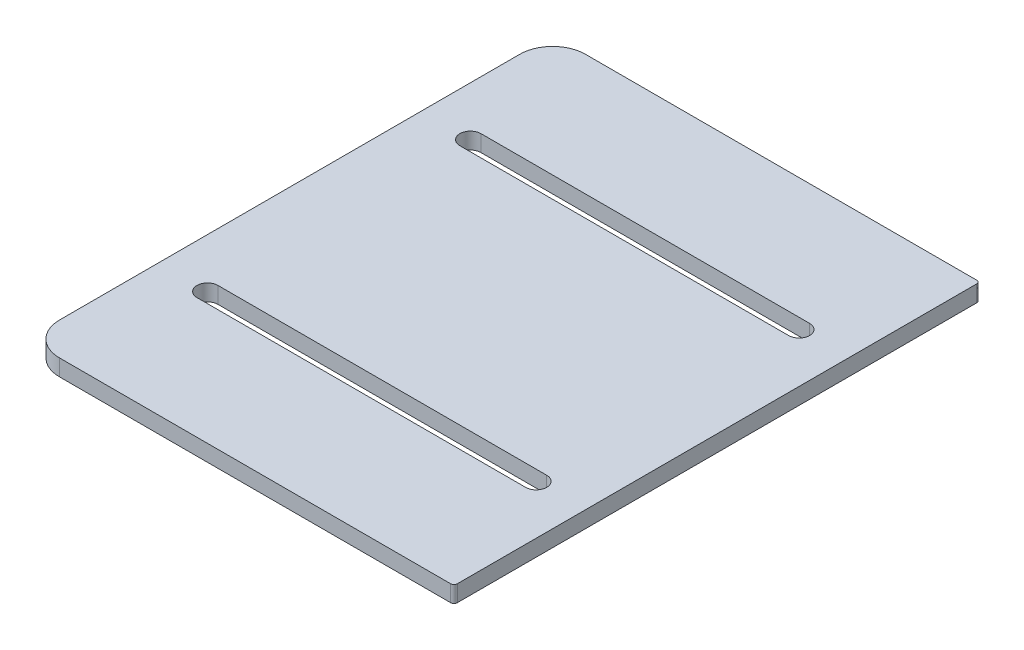
SolidWorks part; units mm, degrees
ref_plane "Front Plane" through (0, 0, 0) normal (0, 0, 1) x (1, 0, 0)
ref_plane "Top Plane" through (0, 0, 0) normal (0, 1, 0) x (1, 0, 0)
ref_plane "Right Plane" through (0, 0, 0) normal (1, 0, 0) x (0, 0, -1)
sketch "Sketch1" plane through (0, 0, 0) normal (0, 1, 0) x (1, 0, 0)
  line L0 (0, 0) -> (28.3099, 0) construction
  line L1 (-82.55, -101.6) -> (82.55, -101.6)
  line L2 (-82.55, -101.6) -> (-82.55, 101.6)
  line L3 (-82.55, 101.6) -> (82.55, 101.6)
  line L4 (82.55, -101.6) -> (82.55, 101.6)
  line L5 (-82.55, -101.6) -> (82.55, 101.6) construction
  line L6 (-82.55, 101.6) -> (82.55, -101.6) construction
  line L7 (-63.5, 54.864) -> (63.5, 54.864)
  line L8 (-63.5, 54.864) -> (-63.5, 46.736)
  line L9 (-63.5, 46.736) -> (63.5, 46.736)
  line L10 (63.5, 54.864) -> (63.5, 46.736)
  line L11 (-63.5, 54.864) -> (63.5, 46.736) construction
  line L12 (-63.5, 46.736) -> (63.5, 54.864) construction
  line L13 (-63.5, -46.736) -> (63.5, -54.864) construction
  line L14 (-63.5, -54.864) -> (63.5, -46.736) construction
  line L15 (63.5, -54.864) -> (63.5, -46.736)
  line L16 (-63.5, -46.736) -> (63.5, -46.736)
  line L17 (-63.5, -54.864) -> (-63.5, -46.736)
  line L18 (-63.5, -54.864) -> (63.5, -54.864)
  circle A0 centre (63.5, 50.8) radius 4.064
  circle A1 centre (-63.5, 50.8) radius 4.064
  circle A2 centre (-63.5, -50.8) radius 4.064
  circle A3 centre (63.5, -50.8) radius 4.064
  point P0 (0, 0)
  point P5 (0, 50.8)
  point P25 (0, -50.8)
  dimension "D3" = 101.6
  dimension "D1" = 165.1
  dimension "D2" = 203.2
  dimension "D4" = 127
  dimension "D5" = 8.128
extrude "Boss-Extrude1" add sketch "Sketch1" along normal blind 6.35 contours L1 L4 L3 L2 A1 L7 A0 L9 L16 A3 L18 A2
fillet "Fillet1" radius 12.7 2 edges at (-82.55, 3.175, -101.6) (-82.55, 3.175, 101.6)
fillet "Fillet2" radius 1.27 2 edges at (82.55, 3.175, 101.6) (82.55, 3.175, -101.6)
